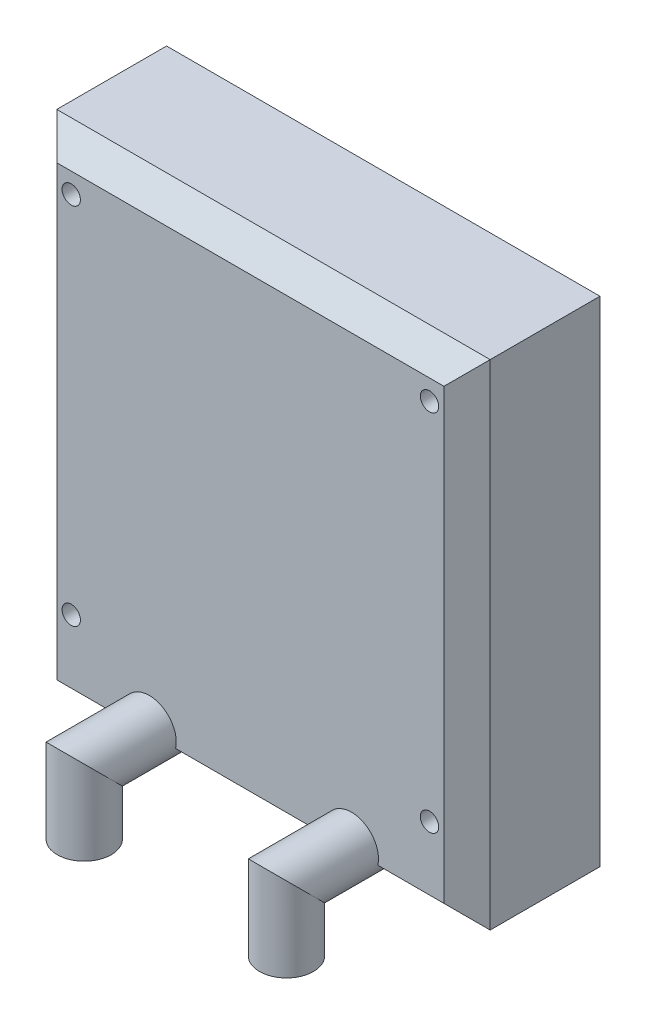
SolidWorks part; units mm, degrees
ref_plane "Front Plane" through (0, 0, 0) normal (0, 0, 1) x (1, 0, 0)
ref_plane "Top Plane" through (0, 0, 0) normal (0, 1, 0) x (1, 0, 0)
ref_plane "Right Plane" through (0, 0, 0) normal (1, 0, 0) x (0, 0, -1)
sketch "Sketch1" plane through (0, 0, 0) normal (0, 0, 1) x (1, 0, 0)
  line L1 (-75, -85.5) -> (75, -85.5)
  line L2 (-75, -85.5) -> (-75, 85.5)
  line L3 (-75, 85.5) -> (75, 85.5)
  line L4 (75, -85.5) -> (75, 85.5)
  line L5 (-75, -85.5) -> (75, 85.5) construction
  line L6 (-75, 85.5) -> (75, -85.5) construction
  point P0 (0, 0)
  dimension "D1" = 150
  dimension "D2" = 171
extrude "Boss-Extrude1" add sketch "Sketch1" along normal blind 54 contours L3 L4 L1 L2
sketch "Sketch2" plane through (0, 0, 54) normal (0, 0, 1) x (1, 0, 0)
  line L0 (-75, 85.5) -> (75, 85.5) construction
  line L1 (-75, -85.5) -> (-75, 85.5) construction
  line L2 (-75, -85.5) -> (75, -85.5) construction
  line L3 (75, -85.5) -> (75, 85.5) construction
  circle A5 centre (-62, 70.5) radius 3.175
  circle A6 centre (62, 70.5) radius 3.175
  circle A7 centre (62, -55.5) radius 3.175
  circle A10 centre (-62, -55.5) radius 3.175
  dimension "D6" = 13
  dimension "D7" = 13
  dimension "D1" = 6.35
  dimension "D2" = 15
  dimension "D4" = 13
  dimension "D5" = 30
  dimension "D3" = 15
  dimension "D8" = 13
extrude "Cut-Extrude1" cut sketch "Sketch2" against normal blind 5.08
ref_plane "Plane1" through (0, 0, 27) normal (0, 0, 1) x (1, 0, 0)
mirror "Mirror1" about plane through (0, 0, 27) normal (0, 0, 1) of "Cut-Extrude1"
sketch "Sketch5" plane through (0, 0, 54) normal (0, 0, 1) x (1, 0, 0)
  line L0 (-75, -85.5) -> (75, -85.5) construction
  line L1 (-75, -85.5) -> (-75, 85.5) construction
  circle A0 centre (-35, -75.5) radius 9.35
  dimension "D3" = 18.7
  dimension "D1" = 10
  dimension "D2" = 40
chamfer "Chamfer1" distance 8 8 edges at (0, 85.5, 0) (-75, 0, 0) (0, -85.5, 0) (75, 0, 0) (0, 85.5, 54) (75, 0, 54) (0, -85.5, 54) (-75, 0, 54)
ref_plane "Plane3" through (0, 0, 0) normal (0, -1, 0) x (-1, 0, 0)
ref_plane "Plane4" through (0, 0, 27) normal (0, 0, -1) x (-1, 0, 0)
ref_plane "Plane6" through (-35, 0, 0) normal (-1, 0, 0) x (0, 0, 1)
sketch "Sketch6" plane through (-35, 0, 0) normal (-1, 0, 0) x (0, 0, 1)
  line L0 (54, -75.5) -> (76.5, -75.5)
  line L1 (76.5, -75.5) -> (76.5, -98)
  line L2 (54, -75.5) -> (44, -75.5)
  dimension "D1" = 22.5
  dimension "D2" = 22.5
  dimension "D3" = 10
sweep "Sweep1" add profiles "Sketch5" path "Sketch6"
ref_plane "Plane7" through (0, 0, 0) normal (-1, 0, 0) x (0, 0, 1)
mirror "Mirror2" about plane through (0, 0, 0) normal (-1, 0, 0) of "Sweep1"
